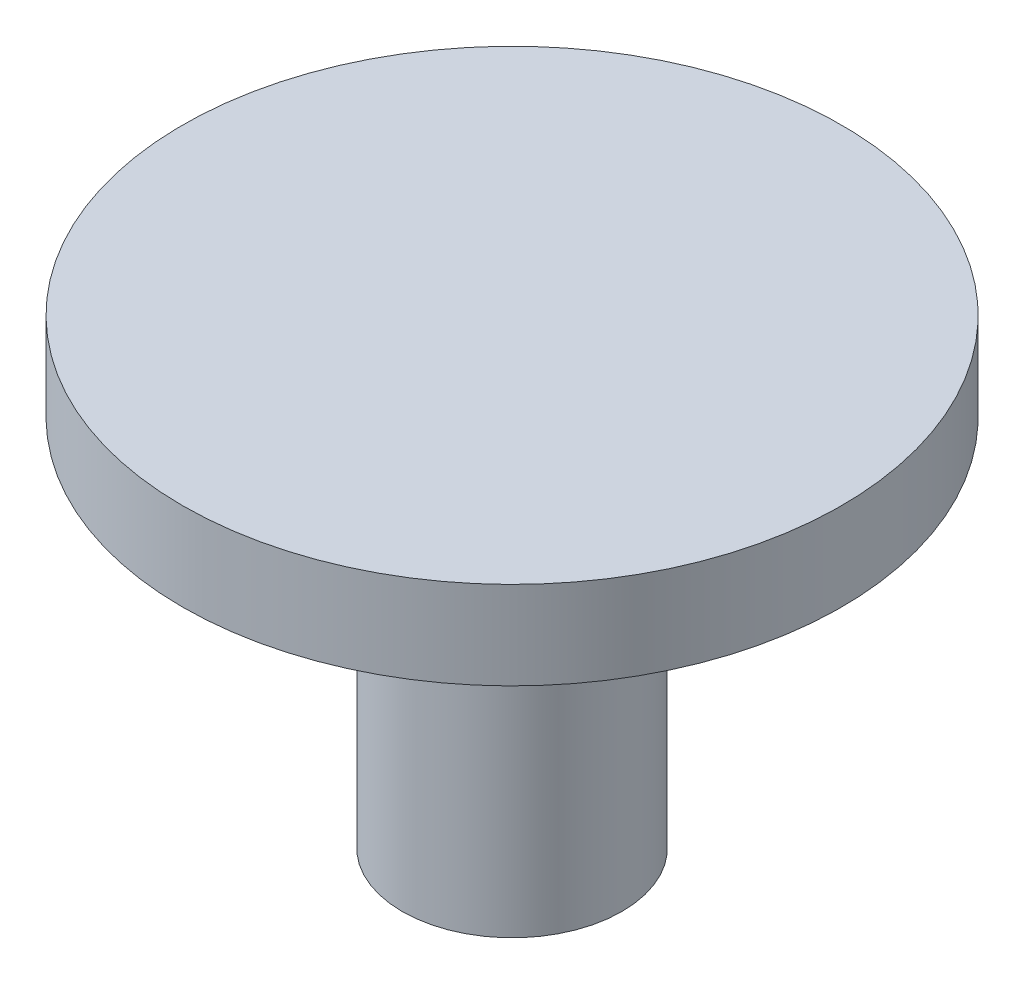
SolidWorks part; units mm, degrees
ref_plane "前视基准面" through (0, 0, 0) normal (0, 0, 1) x (1, 0, 0)
ref_plane "上视基准面" through (0, 0, 0) normal (0, 1, 0) x (1, 0, 0)
ref_plane "右视基准面" through (0, 0, 0) normal (1, 0, 0) x (0, 0, -1)
other "Configuration Table"
sketch "草图1" plane through (0, 0, 0) normal (0, 1, 0) x (1, 0, 0)
  line L0 (2.5773, 1.631) -> (-2.4854, 1.7678)
  circle A0 centre (0, 0) radius 5
  arc A1 (-2.4854, 1.7678) -> (2.5773, 1.631) centre (0, 0) ccw
  dimension "D1" = 10
  dimension "D2" = 6.1
  dimension "D3" = 1.7
extrude "凸台-拉伸1" add sketch "草图1" along normal blind 9
sketch "草图5" plane through (0, 9, 0) normal (0, 1, 0) x (1, 0, 0)
  circle A0 centre (0, 0) radius 5
extrude "凸台-拉伸5" add sketch "草图5" along normal blind 8
sketch "草图6" plane through (0, 17, 0) normal (0, 1, 0) x (1, 0, 0)
  circle A0 centre (0, 0) radius 15
  dimension "D1" = 30
extrude "凸台-拉伸6" add sketch "草图6" along normal blind 4
chamfer "倒角3" distance 1 angle 45 1 edges at (0, 17, 5)
